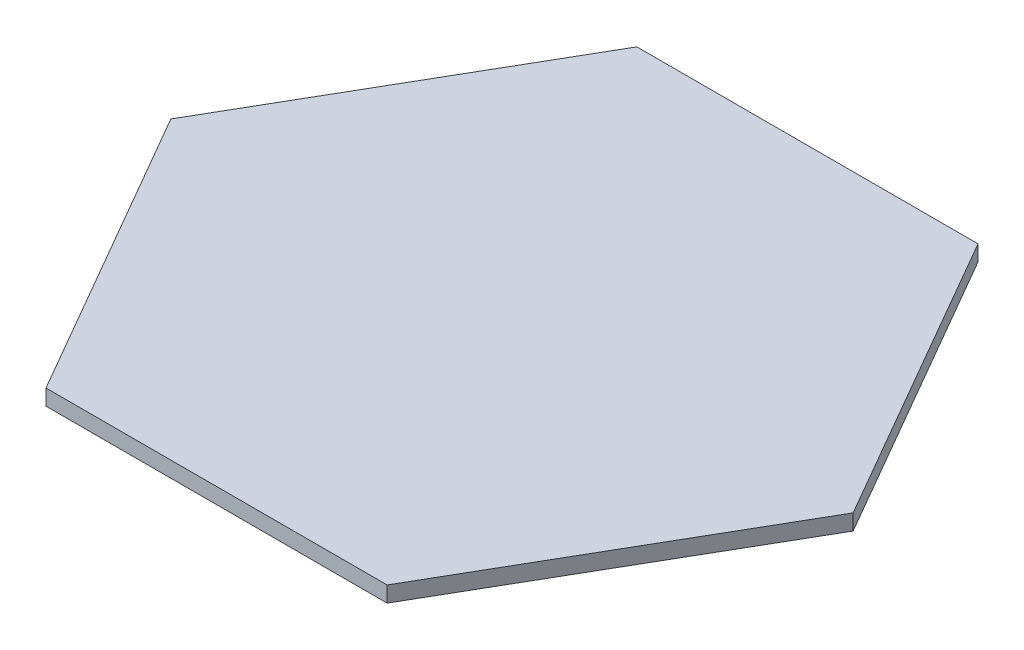
SolidWorks part; units mm, degrees
ref_plane "前视基准面" through (0, 0, 0) normal (0, 0, 1) x (1, 0, 0)
ref_plane "上视基准面" through (0, 0, 0) normal (0, 1, 0) x (1, 0, 0)
ref_plane "右视基准面" through (0, 0, 0) normal (1, 0, 0) x (0, 0, -1)
sketch "草图1" plane through (0, 0, 0) normal (0, 1, 0) x (1, 0, 0)
  line L1 (65, 0) -> (32.5, 56.2917)
  line L2 (32.5, 56.2917) -> (-32.5, 56.2917)
  line L3 (-32.5, 56.2917) -> (-65, 0)
  line L4 (-65, 0) -> (-32.5, -56.2917)
  line L5 (-32.5, -56.2917) -> (32.5, -56.2917)
  line L6 (32.5, -56.2917) -> (65, 0)
  circle A0 centre (0, 0) radius 56.2917 construction
  dimension "D1" = 65
extrude "凸台-拉伸1" add sketch "草图1" along normal blind 3
